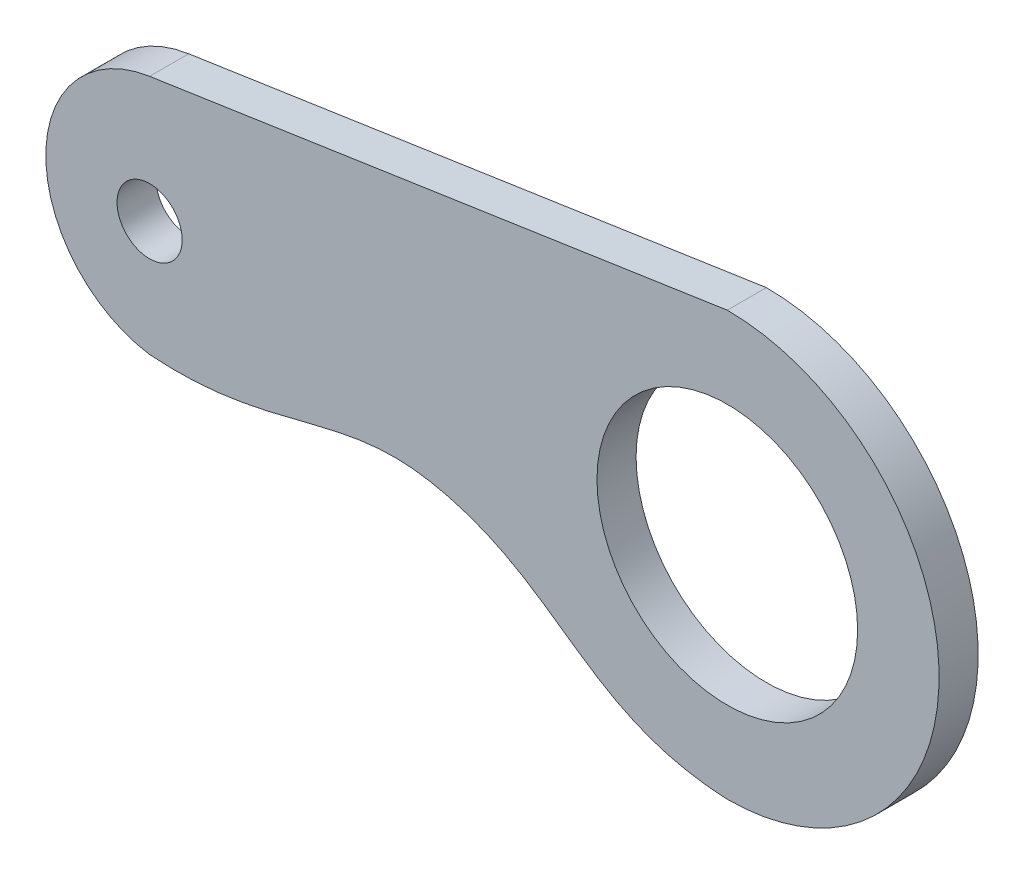
SolidWorks part; units mm, degrees
ref_plane "Спереди" through (0, 0, 0) normal (0, 0, 1) x (1, 0, 0)
ref_plane "Сверху" through (0, 0, 0) normal (0, 1, 0) x (1, 0, 0)
ref_plane "Справа" through (0, 0, 0) normal (1, 0, 0) x (0, 0, -1)
sketch "Эскиз1" plane through (0, 0, 0) normal (0, 0, 1) x (1, 0, 0)
  line L0 (0, 0) -> (-113.9419, 0) construction
  line L1 (-88.6528, 19.249) -> (0, 32.5)
  arc A0 (0, -32.5) -> (0, 32.5) centre (0, 0) ccw
  arc A1 (-88.6528, 19.249) -> (-88.6528, -17.7261) centre (-85.8895, 0.7615) ccw
  circle A2 centre (0, 0) radius 20
  circle A3 centre (-88.6528, 0) radius 5
  circle A4 centre (0, 0) radius 32.5 construction
  spline S0 degree 3 poles (-88.6528, -17.7261) (-70.9127, -19.0485) (-58.6691, -9.5753) (-25.5132, -17.947) (-19.3852, -31.6234) (0, -32.5) knots 0 0 0 0 0.412175 0.512175 1 1 1 1
extrude "Вытянуть1" add sketch "Эскиз1" along normal blind 6
